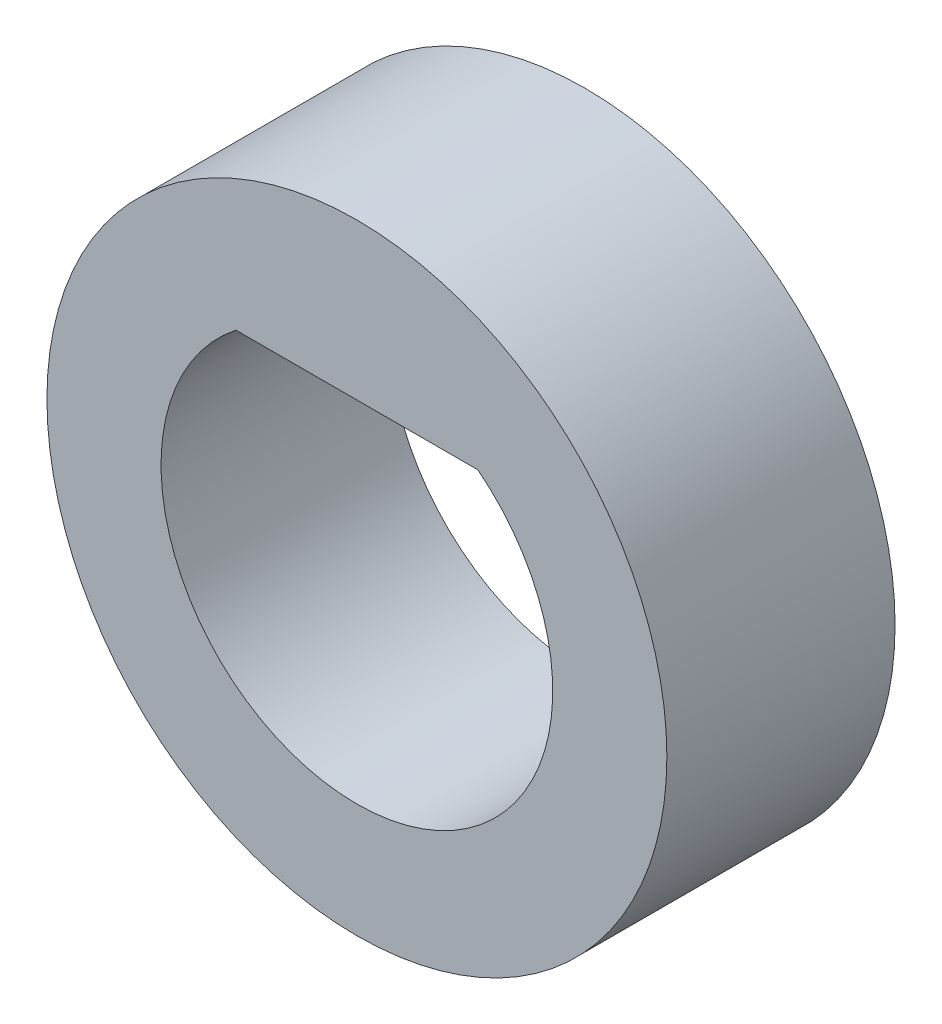
SolidWorks part; units mm, degrees
ref_plane "Front" through (0, 0, 0) normal (0, 0, 1) x (1, 0, 0)
ref_plane "Top" through (0, 0, 0) normal (0, 1, 0) x (1, 0, 0)
ref_plane "Right" through (0, 0, 0) normal (1, 0, 0) x (0, 0, -1)
sketch "Sketch1" plane through (0, 0, 0) normal (0, 0, 1) x (1, 0, 0)
  line L0 (-1.5906, 2.025) -> (1.5906, 2.025)
  line L1 (0, -2.575) -> (0, 2.025) construction
  arc A1 (-1.5906, 2.025) -> (1.5906, 2.025) centre (0, 0) ccw
  circle A2 centre (0, 0) radius 4.075
  arc A3 (1.5906, 2.025) -> (-1.5906, 2.025) centre (0, 0) ccw construction
  dimension "D1" = 1.5
  dimension "D3" = 5.15
  dimension "D2" = 4.6
extrude "Boss-Extrude1" add sketch "Sketch1" along normal blind 3
